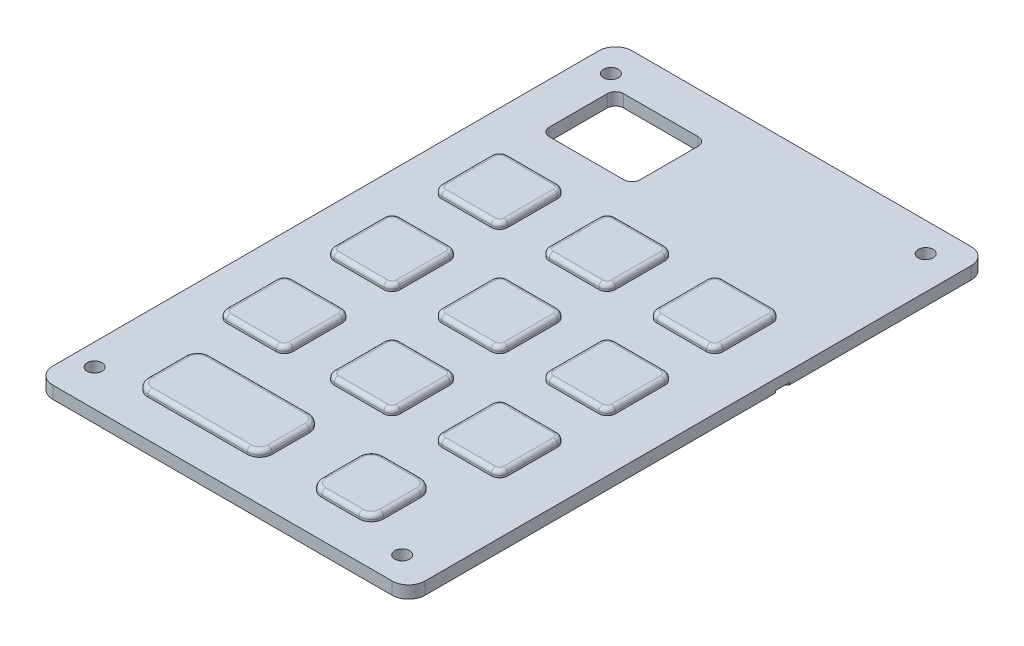
SolidWorks part; units mm, degrees
ref_plane "前基準面" through (0, 0, 0) normal (0, 0, 1) x (1, 0, 0)
ref_plane "上基準面" through (0, 0, 0) normal (0, 1, 0) x (1, 0, 0)
ref_plane "右基準面" through (0, 0, 0) normal (1, 0, 0) x (0, 0, -1)
sketch "草圖1" plane through (0, 0, 0) normal (0, 1, 0) x (1, 0, 0)
  line L1 (-41, -70) -> (41, -70)
  line L2 (-45, -66) -> (-45, 66)
  line L3 (-41, 70) -> (41, 70)
  line L4 (45, -66) -> (45, 66)
  line L5 (-45, -70) -> (45, 70) construction
  line L6 (-45, 70) -> (45, -70) construction
  arc A0 (-45, 66) -> (-41, 70) centre (-41, 66) cw
  arc A1 (41, 70) -> (45, 66) centre (41, 66) cw
  arc A2 (45, -66) -> (41, -70) centre (41, -66) cw
  arc A3 (-45, -66) -> (-41, -70) centre (-41, -66) ccw
  point P0 (0, 0)
  dimension "D3" = 4
  dimension "D1" = 90
  dimension "D2" = 140
extrude "填料-伸長1" add sketch "草圖1" along normal blind 3
sketch "草圖2" plane through (0, 3, 0) normal (0, 1, 0) x (1, 0, 0)
  line L0 (41, 70) -> (-41, 70) construction
  line L1 (-33, 60) -> (-15, 60)
  line L2 (-35, 58) -> (-35, 44)
  line L3 (-33, 42) -> (-15, 42)
  line L4 (-13, 58) -> (-13, 44)
  line L5 (-45, 66) -> (-45, -66) construction
  arc A0 (-35, 44) -> (-33, 42) centre (-33, 44) ccw
  arc A1 (-15, 42) -> (-13, 44) centre (-15, 44) ccw
  arc A2 (-13, 58) -> (-15, 60) centre (-15, 58) ccw
  arc A3 (-35, 58) -> (-33, 60) centre (-33, 58) cw
  point P10 (-13, 42)
  point P13 (-13, 60)
  point P16 (-35, 60)
  dimension "D4" = 2
  dimension "D1" = 18
  dimension "D2" = 22
  dimension "D3" = 10
  dimension "D5" = 10
extrude "除料-伸長1" cut sketch "草圖2" against normal blind 15
sketch "草圖3" plane through (0, 3, 0) normal (0, 1, 0) x (1, 0, 0)
  line L0 (-14, 71.0732) -> (-14, -20.3858) construction
  line L1 (-33, 32) -> (-21, 32)
  line L2 (-35, 30) -> (-35, 18)
  line L3 (-33, 16) -> (-21, 16)
  line L4 (-19, 30) -> (-19, 18)
  line L5 (5, 16) -> (-7, 16)
  line L6 (7, 30) -> (7, 18)
  line L7 (-9, 30) -> (-9, 18)
  line L8 (5, 32) -> (-7, 32)
  line L9 (12, 67.0574) -> (12, -25.755) construction
  line L10 (19, 16) -> (31, 16)
  line L11 (33, 30) -> (33, 18)
  line L12 (17, 30) -> (17, 18)
  line L13 (19, 32) -> (31, 32)
  line L14 (-57.0684, 11) -> (59.1492, 11) construction
  line L15 (19, 6) -> (31, 6)
  line L16 (33, -8) -> (33, 4)
  line L17 (17, -8) -> (17, 4)
  line L18 (19, -10) -> (31, -10)
  line L19 (-9, -8) -> (-9, 4)
  line L20 (5, 6) -> (-7, 6)
  line L21 (7, -8) -> (7, 4)
  line L22 (5, -10) -> (-7, -10)
  line L23 (-33, -10) -> (-21, -10)
  line L24 (-19, -8) -> (-19, 4)
  line L25 (-35, -8) -> (-35, 4)
  line L26 (-33, 6) -> (-21, 6)
  line L27 (-55.3294, -15) -> (60.8882, -15) construction
  line L28 (19, -20) -> (31, -20)
  line L29 (17, -22) -> (17, -34)
  line L30 (33, -22) -> (33, -34)
  line L31 (19, -36) -> (31, -36)
  line L32 (5, -20) -> (-7, -20)
  line L33 (7, -22) -> (7, -34)
  line L34 (5, -36) -> (-7, -36)
  line L35 (-9, -22) -> (-9, -34)
  line L36 (-33, -36) -> (-21, -36)
  line L37 (-35, -22) -> (-35, -34)
  line L38 (-19, -22) -> (-19, -34)
  line L39 (-33, -20) -> (-21, -20)
  line L40 (-33, 42) -> (-15, 42) construction
  line L41 (-45, 66) -> (-45, -66) construction
  line L79 (-27, -61) -> (-3, -61)
  line L80 (-30, -58) -> (-30, -49)
  line L81 (-27, -46) -> (-3, -46)
  line L82 (0, -58) -> (0, -49)
  line L85 (15, -61) -> (24, -61)
  line L86 (12, -58) -> (12, -49)
  line L87 (15, -46) -> (24, -46)
  line L88 (27, -58) -> (27, -49)
  arc A0 (-19, 18) -> (-21, 16) centre (-21, 18) cw
  arc A1 (-33, 16) -> (-35, 18) centre (-33, 18) cw
  arc A2 (-35, 30) -> (-33, 32) centre (-33, 30) cw
  arc A3 (-19, 30) -> (-21, 32) centre (-21, 30) ccw
  arc A4 (-9, 18) -> (-7, 16) centre (-7, 18) ccw
  arc A5 (5, 16) -> (7, 18) centre (5, 18) ccw
  arc A6 (7, 30) -> (5, 32) centre (5, 30) ccw
  arc A7 (-9, 30) -> (-7, 32) centre (-7, 30) cw
  arc A8 (19, 16) -> (17, 18) centre (19, 18) cw
  arc A9 (33, 18) -> (31, 16) centre (31, 18) cw
  arc A10 (33, 30) -> (31, 32) centre (31, 30) ccw
  arc A11 (17, 30) -> (19, 32) centre (19, 30) cw
  arc A12 (19, 6) -> (17, 4) centre (19, 4) ccw
  arc A13 (33, 4) -> (31, 6) centre (31, 4) ccw
  arc A14 (33, -8) -> (31, -10) centre (31, -8) cw
  arc A15 (17, -8) -> (19, -10) centre (19, -8) ccw
  arc A16 (-9, -8) -> (-7, -10) centre (-7, -8) ccw
  arc A17 (-9, 4) -> (-7, 6) centre (-7, 4) cw
  arc A18 (5, 6) -> (7, 4) centre (5, 4) cw
  arc A19 (7, -8) -> (5, -10) centre (5, -8) cw
  arc A20 (-35, -8) -> (-33, -10) centre (-33, -8) ccw
  arc A21 (-33, 6) -> (-35, 4) centre (-33, 4) ccw
  arc A22 (-19, -8) -> (-21, -10) centre (-21, -8) cw
  arc A23 (-19, 4) -> (-21, 6) centre (-21, 4) ccw
  arc A24 (17, -22) -> (19, -20) centre (19, -22) cw
  arc A25 (33, -22) -> (31, -20) centre (31, -22) ccw
  arc A26 (33, -34) -> (31, -36) centre (31, -34) cw
  arc A27 (19, -36) -> (17, -34) centre (19, -34) cw
  arc A28 (7, -22) -> (5, -20) centre (5, -22) ccw
  arc A29 (5, -36) -> (7, -34) centre (5, -34) ccw
  arc A30 (-9, -34) -> (-7, -36) centre (-7, -34) ccw
  arc A31 (-9, -22) -> (-7, -20) centre (-7, -22) cw
  arc A32 (-19, -34) -> (-21, -36) centre (-21, -34) cw
  arc A33 (-19, -22) -> (-21, -20) centre (-21, -22) ccw
  arc A34 (-33, -36) -> (-35, -34) centre (-33, -34) cw
  arc A35 (-35, -22) -> (-33, -20) centre (-33, -22) cw
  arc A72 (-27, -61) -> (-30, -58) centre (-27, -58) cw
  arc A73 (-3, -61) -> (0, -58) centre (-3, -58) ccw
  arc A74 (0, -49) -> (-3, -46) centre (-3, -49) ccw
  arc A75 (-30, -49) -> (-27, -46) centre (-27, -49) cw
  arc A76 (12, -58) -> (15, -61) centre (15, -58) ccw
  arc A77 (24, -61) -> (27, -58) centre (24, -58) ccw
  arc A78 (24, -46) -> (27, -49) centre (24, -49) cw
  arc A79 (15, -46) -> (12, -49) centre (15, -49) ccw
  point P6 (-19, 16)
  point P11 (-35, 32)
  point P14 (-19, 32)
  point P261 (-30, -61)
  point P266 (0, -46)
  point P269 (-30, -46)
  point P280 (27, -46)
  point P283 (12, -46)
  dimension "D3" = 15
  dimension "D19" = 3
  dimension "D21" = 3
  dimension "D1" = 16
  dimension "D2" = 16
  dimension "D4" = 5
  dimension "D5" = 5
  dimension "D6" = 5
  dimension "D7" = 5
  dimension "D8" = 18
  dimension "D9" = 10
  dimension "D10" = 10
  dimension "D11" = 12
  dimension "D15" = 30
  dimension "D16" = 15
  dimension "D17" = 10
  dimension "D20" = 15
  dimension "D22" = 10
  dimension "D23" = 15
sketch "草圖5" plane through (0, 0, 0) normal (0, -1, 0) x (1, 0, 0)
extrude "填料-伸長2" add sketch "草圖3" along normal blind 1.5
sketch "草圖7" plane through (0, 4.5, 0) normal (0, 1, 0) x (1, 0, 0)
fillet "圓角2" radius 1 8 edges at (-19.5858, 4.5, -16.5858) (-19, 4.5, -24) (-19.5858, 4.5, -31.4142) (-27, 4.5, -32) (-34.4142, 4.5, -31.4142) (-35, 4.5, -24) (-34.4142, 4.5, -16.5858) (-27, 4.5, -16)
fillet "圓角3" radius 1 8 edges at (-8.4142, 4.5, -16.5858) (-1, 4.5, -16) (6.4142, 4.5, -16.5858) (7, 4.5, -24) (6.4142, 4.5, -31.4142) (-1, 4.5, -32) (-8.4142, 4.5, -31.4142) (-9, 4.5, -24)
fillet "圓角4" radius 1 8 edges at (12.8787, 4.5, 60.1213) (19.5, 4.5, 61) (26.1213, 4.5, 60.1213) (27, 4.5, 53.5) (26.1213, 4.5, 46.8787) (19.5, 4.5, 46) (12.8787, 4.5, 46.8787) (12, 4.5, 53.5)
fillet "圓角5" radius 1 8 edges at (17.5858, 4.5, 20.5858) (17, 4.5, 28) (17.5858, 4.5, 35.4142) (25, 4.5, 36) (32.4142, 4.5, 35.4142) (33, 4.5, 28) (32.4142, 4.5, 20.5858) (25, 4.5, 20)
fillet "圓角6" radius 1 8 edges at (6.4142, 4.5, 20.5858) (-1, 4.5, 20) (-8.4142, 4.5, 20.5858) (-9, 4.5, 28) (-8.4142, 4.5, 35.4142) (-1, 4.5, 36) (6.4142, 4.5, 35.4142) (7, 4.5, 28)
fillet "圓角7" radius 1 8 edges at (-19.5858, 4.5, 35.4142) (-19, 4.5, 28) (-19.5858, 4.5, 20.5858) (-27, 4.5, 20) (-34.4142, 4.5, 20.5858) (-35, 4.5, 28) (-34.4142, 4.5, 35.4142) (-27, 4.5, 36)
fillet "圓角8" radius 1 8 edges at (-34.4142, 4.5, 9.4142) (-27, 4.5, 10) (-19.5858, 4.5, 9.4142) (-19, 4.5, 2) (-19.5858, 4.5, -5.4142) (-27, 4.5, -6) (-34.4142, 4.5, -5.4142) (-35, 4.5, 2)
fillet "圓角9" radius 1 8 edges at (-29.1213, 4.5, 60.1213) (-15, 4.5, 61) (-0.8787, 4.5, 60.1213) (0, 4.5, 53.5) (-0.8787, 4.5, 46.8787) (-15, 4.5, 46) (-29.1213, 4.5, 46.8787) (-30, 4.5, 53.5)
fillet "圓角10" radius 1 8 edges at (17.5858, 4.5, -5.4142) (17, 4.5, 2) (17.5858, 4.5, 9.4142) (25, 4.5, 10) (32.4142, 4.5, 9.4142) (33, 4.5, 2) (32.4142, 4.5, -5.4142) (25, 4.5, -6)
fillet "圓角11" radius 1 8 edges at (17.5858, 4.5, -16.5858) (25, 4.5, -16) (32.4142, 4.5, -16.5858) (33, 4.5, -24) (32.4142, 4.5, -31.4142) (25, 4.5, -32) (17.5858, 4.5, -31.4142) (17, 4.5, -24)
fillet "圓角12" radius 1 8 edges at (-8.4142, 4.5, 9.4142) (-1, 4.5, 10) (6.4142, 4.5, 9.4142) (7, 4.5, 2) (6.4142, 4.5, -5.4142) (-1, 4.5, -6) (-8.4142, 4.5, -5.4142) (-9, 4.5, 2)
sketch "草圖8" plane through (0, 3, 0) normal (0, 1, 0) x (1, 0, 0)
  circle A0 centre (36.9835, 63.0221) radius 1.8
  arc A1 (45, 66) -> (41, 70) centre (41, 66) ccw construction
  circle A2 centre (36.783, -63.3136) radius 1.8
  arc A4 (41, -70) -> (45, -66) centre (41, -66) ccw construction
  circle A5 centre (-39.7443, -61.1603) radius 1.8
  arc A6 (-45, -66) -> (-41, -70) centre (-41, -66) ccw construction
  circle A7 centre (-38.7779, 62.674) radius 1.8
  arc A8 (-41, 70) -> (-45, 66) centre (-41, 66) ccw construction
  dimension "D1" = 5
  dimension "D2" = 3.6
  dimension "D3" = 3.6
  dimension "D4" = 5
  dimension "D5" = 3.6
  dimension "D6" = 5
  dimension "D7" = 3.6
  dimension "D8" = 4
extrude "除料-伸長2" cut sketch "草圖8" against normal blind 5
sketch "Sketch1" plane through (0, 0, 0) normal (0, -1, 0) x (1, 0, 0)
  line L0 (-39.0903, 59.4833) -> (45, -22.062)
  line L1 (-39.0903, 59.4833) -> (-39.0903, 62.8372)
  line L2 (45, -22.062) -> (45, -18.7081)
  line L3 (-39.0903, 62.8372) -> (45, -18.7081)
  line L5 (45, 66) -> (45, -66) construction
  circle A0 centre (-39.7443, 61.1603) radius 1.8 construction
extrude "Cut-Extrude1" cut sketch "Sketch1" against normal blind 0.5
